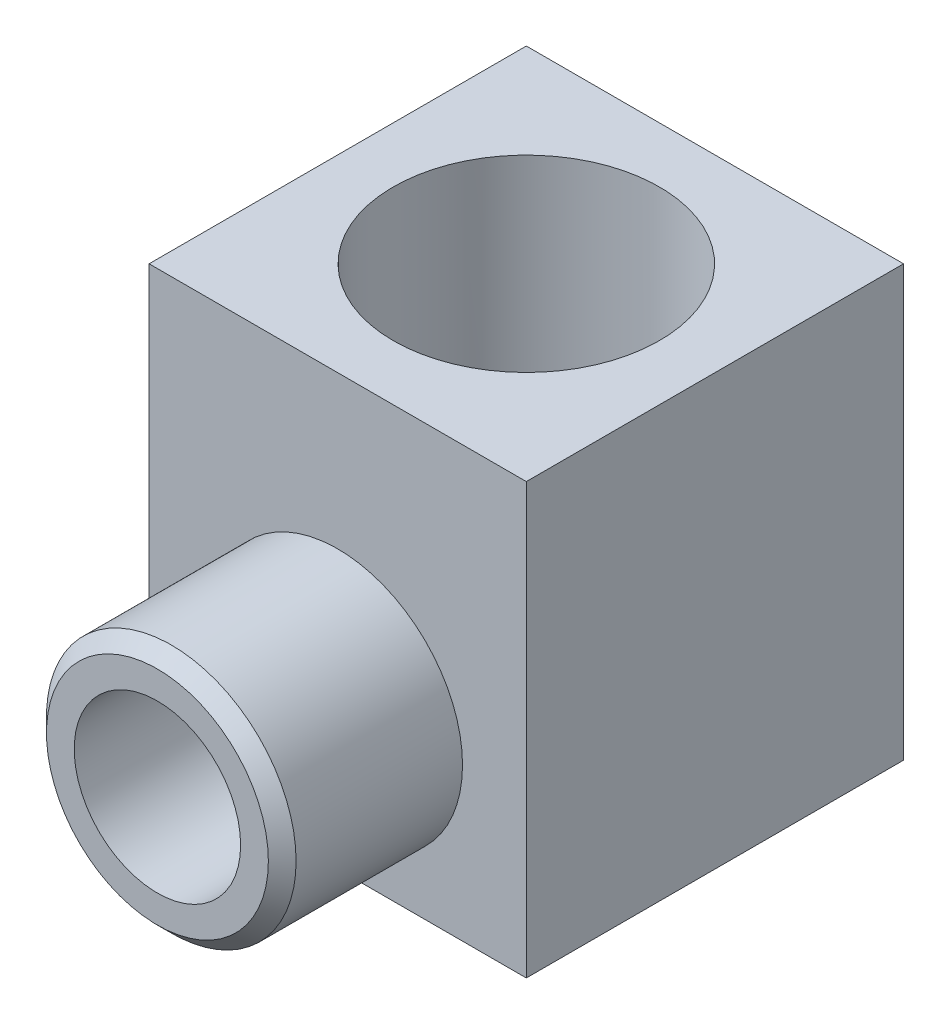
SolidWorks part; units mm, degrees
ref_plane "Front Plane" through (0, 0, 0) normal (0, 0, 1) x (1, 0, 0)
ref_plane "Top Plane" through (0, 0, 0) normal (0, 1, 0) x (1, 0, 0)
ref_plane "Right Plane" through (0, 0, 0) normal (1, 0, 0) x (0, 0, -1)
sketch "Sketch1" plane through (0, 0, 0) normal (0, 0, 1) x (1, 0, 0)
  circle A0 centre (0, 0) radius 12.8
extrude "Boss-Extrude1" add sketch "Sketch1" along normal blind 20.1
sketch "Sketch2" plane through (0, 0, 20.1) normal (0, 0, 1) x (1, 0, 0)
  circle A0 centre (0, 0) radius 4.5
extrude "Cut-Extrude1" cut sketch "Sketch2" against normal blind 6.5 flip side to cut
chamfer "Chamfer1" distance 0.5 angle 45 1 edges at (4.5, 0, 20.1)
sketch "Sketch3" plane through (0, 0, 20.1) normal (0, 0, 1) x (1, 0, 0)
  circle A0 centre (0, 0) radius 3
extrude "Cut-Extrude2" cut sketch "Sketch3" against normal blind 10
sketch "Sketch4" plane through (0, 0, 13.6) normal (0, 0, 1) x (1, 0, 0)
  line L0 (-6.8, 10) -> (6.8, 10)
  line L1 (-6.8, -5.5) -> (6.8, -5.5)
  line L5 (-6.8, -5.5) -> (-6.8, 10)
  line L6 (6.8, -5.5) -> (6.8, 10)
extrude "Cut-Extrude3" cut sketch "Sketch4" against normal up to surface (13.6 mm away) flip side to cut up to face at (12.8, 0, 0)
sketch "Sketch5" plane through (0, 10, 0) normal (0, 1, 0) x (1, 0, 0)
  circle A0 centre (0, -6.8) radius 4.8
extrude "Cut-Extrude4" cut sketch "Sketch5" against normal offset from surface (13.5 mm away) 2 up to face at (0, -5.5, 6.8)
